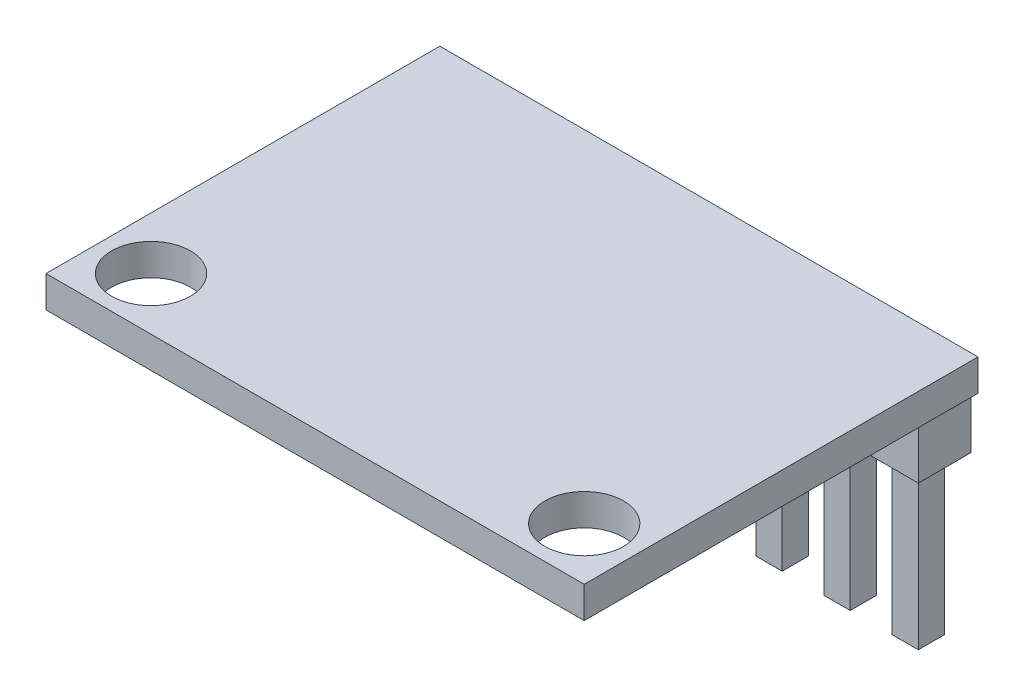
SolidWorks part; units mm, degrees
ref_plane "Front Plane" through (0, 0, 0) normal (0, 0, 1) x (1, 0, 0)
ref_plane "Top Plane" through (0, 0, 0) normal (0, 1, 0) x (1, 0, 0)
ref_plane "Right Plane" through (0, 0, 0) normal (1, 0, 0) x (0, 0, -1)
sketch "Sketch1" plane through (0, 0, 0) normal (0, 1, 0) x (1, 0, 0)
  line L0 (0, 0) -> (0, -7.5) construction
  line L1 (10.25, -7.5) -> (-10.25, -7.5)
  line L2 (10.25, -7.5) -> (10.25, 7.5)
  line L3 (10.25, 7.5) -> (-10.25, 7.5)
  line L4 (-10.25, -7.5) -> (-10.25, 7.5)
  line L5 (10.25, -7.5) -> (-10.25, 7.5) construction
  line L6 (10.25, 7.5) -> (-10.25, -7.5) construction
  circle A0 centre (-8.25, -5.5) radius 1.5
  circle A1 centre (8.25, -5.5) radius 1.5
  point P0 (0, 0)
  dimension "D3" = 3
  dimension "D1" = 20.5
  dimension "D2" = 15
  dimension "D4" = 2
  dimension "D5" = 2
extrude "Boss-Extrude1" add sketch "Sketch1" along normal blind 1.2
sketch "Sketch2" plane through (0, 0, 0) normal (0, 1, 0) x (1, 0, 0)
  line L0 (10.25, 6.4) -> (-10.25, 6.4) construction
  line L1 (10.25, -7.5) -> (10.25, 7.5) construction
  line L2 (-10.25, 7.5) -> (-10.25, -7.5) construction
  line L3 (10.25, 7.5) -> (-10.25, 7.5) construction
  line L4 (8.575, 5.9) -> (9.575, 5.9)
  line L5 (8.575, 5.9) -> (8.575, 6.9)
  line L6 (8.575, 6.9) -> (9.575, 6.9)
  line L7 (9.575, 5.9) -> (9.575, 6.9)
  line L8 (8.575, 5.9) -> (9.575, 6.9) construction
  line L9 (8.575, 6.9) -> (9.575, 5.9) construction
  line L10 (5.9825, 5.9) -> (5.9825, 6.9)
  line L11 (5.9825, 5.9) -> (6.9825, 5.9)
  line L12 (6.9825, 5.9) -> (6.9825, 6.9)
  line L13 (5.9825, 6.9) -> (6.9825, 6.9)
  line L14 (3.39, 5.9) -> (3.39, 6.9)
  line L15 (3.39, 5.9) -> (4.39, 5.9)
  line L16 (4.39, 5.9) -> (4.39, 6.9)
  line L17 (3.39, 6.9) -> (4.39, 6.9)
  line L18 (0.7975, 5.9) -> (0.7975, 6.9)
  line L19 (0.7975, 5.9) -> (1.7975, 5.9)
  line L20 (1.7975, 5.9) -> (1.7975, 6.9)
  line L21 (0.7975, 6.9) -> (1.7975, 6.9)
  line L22 (-1.795, 5.9) -> (-1.795, 6.9)
  line L23 (-1.795, 5.9) -> (-0.795, 5.9)
  line L24 (-0.795, 5.9) -> (-0.795, 6.9)
  line L25 (-1.795, 6.9) -> (-0.795, 6.9)
  line L26 (-4.3875, 5.9) -> (-4.3875, 6.9)
  line L27 (-4.3875, 5.9) -> (-3.3875, 5.9)
  line L28 (-3.3875, 5.9) -> (-3.3875, 6.9)
  line L29 (-4.3875, 6.9) -> (-3.3875, 6.9)
  line L30 (-6.98, 5.9) -> (-6.98, 6.9)
  line L31 (-6.98, 5.9) -> (-5.98, 5.9)
  line L32 (-5.98, 5.9) -> (-5.98, 6.9)
  line L33 (-6.98, 6.9) -> (-5.98, 6.9)
  line L34 (-9.5725, 5.9) -> (-9.5725, 6.9)
  line L35 (-9.5725, 5.9) -> (-8.5725, 5.9)
  line L36 (-8.5725, 5.9) -> (-8.5725, 6.9)
  line L37 (-9.5725, 6.9) -> (-8.5725, 6.9)
  point P6 (9.075, 6.4)
  dimension "D1" = 1
  dimension "D2" = 1
  dimension "D3" = 1.175
  dimension "D4" = 1.1
  dimension "D5" = 8
extrude "Boss-Extrude2" add sketch "Sketch2" against normal blind 8
sketch "Sketch3" plane through (0, 0, 0) normal (0, 1, 0) x (1, 0, 0)
  line L0 (9.575, 5.9) -> (9.575, 6.9) construction
  line L1 (-10.075, 5.4) -> (10.075, 5.4)
  line L2 (-10.075, 5.4) -> (-10.075, 7.4)
  line L3 (-10.075, 7.4) -> (10.075, 7.4)
  line L4 (10.075, 5.4) -> (10.075, 7.4)
  line L5 (-10.075, 5.4) -> (10.075, 7.4) construction
  line L6 (-10.075, 7.4) -> (10.075, 5.4) construction
  line L7 (1.7975, 6.9) -> (0.7975, 6.9) construction
  line L8 (0.7975, 5.9) -> (1.7975, 5.9) construction
  point P0 (0, 6.4)
  point P11 (0, 0)
  dimension "D1" = 0.5
  dimension "D2" = 0.5
  dimension "D3" = 0.5
extrude "Boss-Extrude3" add sketch "Sketch3" against normal blind 2
